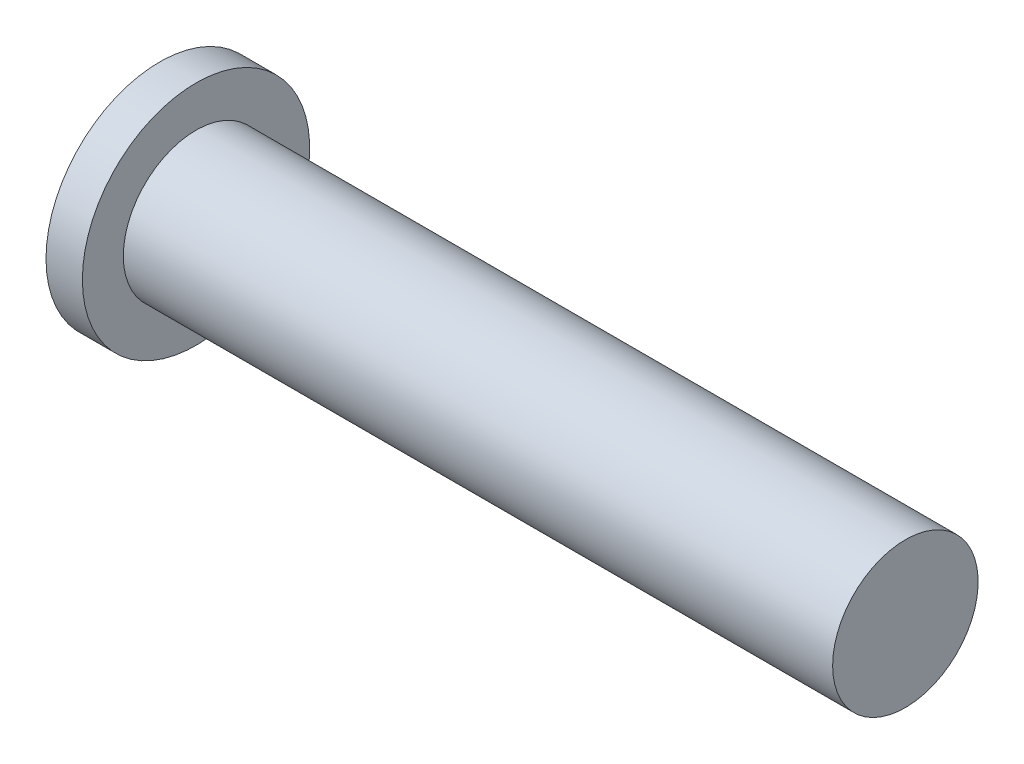
SolidWorks part; units mm, degrees
ref_plane "正面" through (0, 0, 0) normal (0, 0, 1) x (1, 0, 0)
ref_plane "平面" through (0, 0, 0) normal (0, 1, 0) x (1, 0, 0)
ref_plane "右側面" through (0, 0, 0) normal (1, 0, 0) x (0, 0, -1)
sketch "ｽｹｯﾁ1" plane through (0, 0, 0) normal (0, 1, 0) x (1, 0, 0)
  line L0 (0, 0) -> (146.5281, 0) construction
  line L1 (0, 0) -> (0, 6.25)
  line L2 (0, 6.25) -> (2, 6.25)
  line L3 (2, 6.25) -> (2, 4)
  line L4 (2, 4) -> (41, 4)
  line L5 (41, 4) -> (41, 0)
  line L6 (41, 0) -> (0, 0)
  dimension "D1" = 6.25
  dimension "D2" = 41
  dimension "D3" = 2
  dimension "D4" = 4
revolve "回転1" add sketch "ｽｹｯﾁ1" angle 360 about L0
